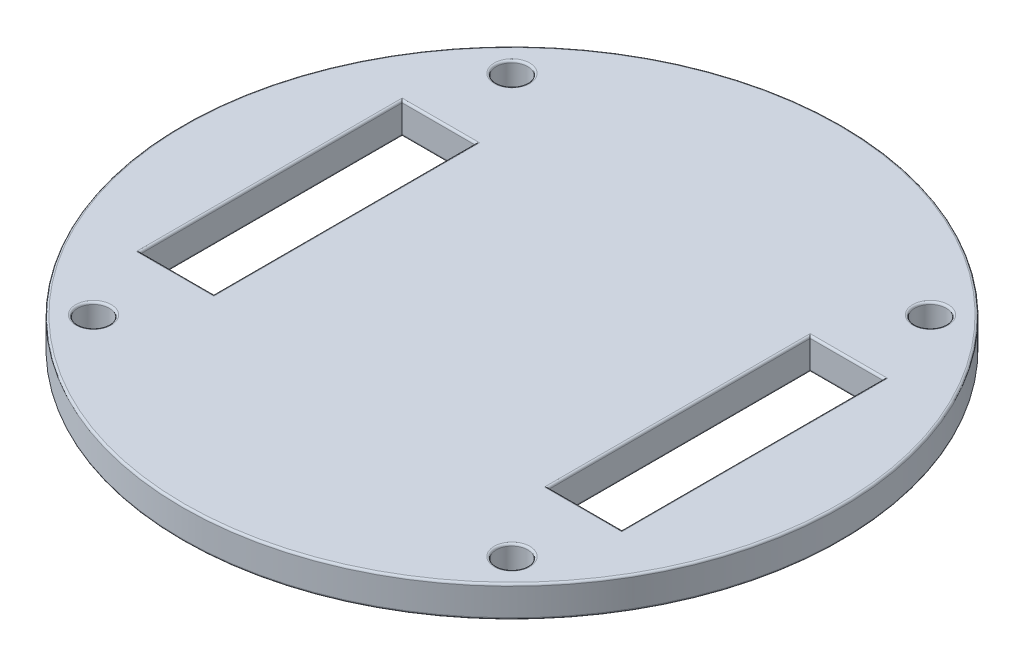
SolidWorks part; units mm, degrees
ref_plane "Front Plane" through (0, 0, 0) normal (0, 0, 1) x (1, 0, 0)
ref_plane "Top Plane" through (0, 0, 0) normal (0, 1, 0) x (1, 0, 0)
ref_plane "Right Plane" through (0, 0, 0) normal (1, 0, 0) x (0, 0, -1)
sketch "Sketch1" plane through (0, 0, 0) normal (0, 1, 0) x (1, 0, 0)
  circle A0 centre (0, 0) radius 31.5
  dimension "D1" = 63
extrude "Boss-Extrude1" add sketch "Sketch1" along normal blind 3
sketch "Sketch2" plane through (0, 3, 0) normal (0, 1, 0) x (1, 0, 0)
  line L0 (0, -1.65) -> (0, 1.65) construction
  line L1 (-23, 12.5) -> (-16, 12.5)
  line L2 (-23, 12.5) -> (-23, -12.5)
  line L3 (-23, -12.5) -> (-16, -12.5)
  line L4 (-16, 12.5) -> (-16, -12.5)
  line L5 (23, -12.5) -> (16, -12.5)
  line L6 (16, 12.5) -> (16, -12.5)
  line L7 (23, 12.5) -> (16, 12.5)
  line L8 (23, 12.5) -> (23, -12.5)
  point P4 (-16, 0)
  dimension "D1" = 25
  dimension "D2" = 7
  dimension "D3" = 16
extrude "Cut-Extrude1" cut sketch "Sketch2" against normal up to next
sketch "Sketch3" plane through (0, 3, 0) normal (0, 1, 0) x (1, 0, 0)
  line L0 (0, -1.65) -> (0, 1.65) construction
  line L1 (-1.65, 0) -> (1.65, 0) construction
  circle A6 centre (-20, -20) radius 1.5
  circle A10 centre (20, -20) radius 1.5
  circle A11 centre (20, 20) radius 1.5
  circle A12 centre (-20, 20) radius 1.5
  dimension "D1" = 3
  dimension "D2" = 20
  dimension "D3" = 20
extrude "Cut-Extrude2" cut sketch "Sketch3" against normal up to next
fillet "Fillet1" radius 0.2 26 edges at (0, 0, 31.5) (16, 0, 0) (19.5, 0, -12.5) (23, 0, 0) (19.5, 0, 12.5) (-16, 0, 0) (-19.5, 0, 12.5) (-23, 0, 0) (-19.5, 0, -12.5) (-20, 0, 21.5) (20, 0, 21.5) (20, 0, -18.5) (-20, 0, -18.5) (0, 3, 31.5) (19.5, 3, -12.5) (16, 3, 0) (19.5, 3, 12.5) (23, 3, 0) (-19.5, 3, 12.5) (-16, 3, 0) (-19.5, 3, -12.5) (-23, 3, 0) (-20, 3, 21.5) (20, 3, 18.5) (20, 3, -18.5) (-20, 3, -21.5)
equation "\"D3@Sketch3\"=\"D2@Sketch3\""
